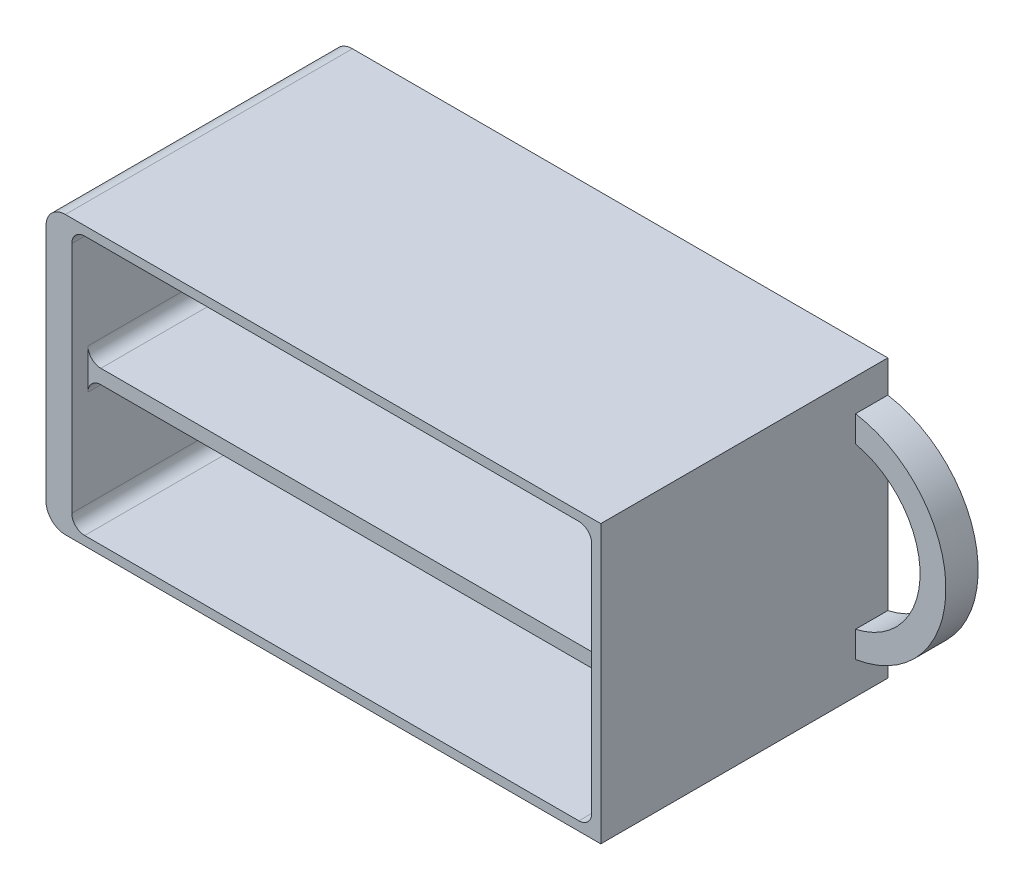
SolidWorks part; units mm, degrees
ref_plane "Спереди" through (0, 0, 0) normal (0, 0, 1) x (1, 0, 0)
ref_plane "Сверху" through (0, 0, 0) normal (0, 1, 0) x (1, 0, 0)
ref_plane "Справа" through (0, 0, 0) normal (1, 0, 0) x (0, 0, -1)
ref_plane "Плоскость4" through (0, 0, 22.25) normal (0, 0, 1) x (1, 0, 0)
sketch "Эскиз1" plane through (0, 0, 22.25) normal (0, 0, 1) x (1, 0, 0)
  line L0 (90, -21.5) -> (90, 21.5)
  line L1 (90, 21.5) -> (4, 21.5)
  line L2 (4, 21.5) -> (4, -21.5)
  line L3 (4, -21.5) -> (90, -21.5)
extrude "Бобышка-Вытянуть1" add sketch "Эскиз1" against normal blind 39.5
sketch "Эскиз2" plane through (0, 0, -17.25) normal (0, 0, -1) x (-1, 0, 0)
  line L0 (-90, -21.5) -> (-90, -16.5)
  line L1 (-90, 16.5) -> (-90, 21.5)
  line L2 (-90, 21.5) -> (-4, 21.5)
  line L3 (-4, 21.5) -> (-4, -21.5)
  line L4 (-4, -21.5) -> (-90, -21.5)
  line L5 (-90, -12.4284) -> (-90, 12.4284)
  arc A0 (-90, -16.5) -> (-90, 16.5) centre (-87.2768, 0) cw
  arc A1 (-90, 12.4284) -> (-90, -12.4284) centre (-87.2768, 0) ccw
extrude "Бобышка-Вытянуть2" add sketch "Эскиз2" along normal blind 5
sketch "Эскиз3" plane through (0, 0, 22.25) normal (0, 0, 1) x (1, 0, 0)
  line L0 (88.6, -20.1) -> (88.6, 20.1)
  line L1 (88.6, 20.1) -> (8, 20.1)
  line L2 (8, 20.1) -> (8, -20.1)
  line L3 (8, -20.1) -> (88.6, -20.1)
extrude "Вырез-Вытянуть1" cut sketch "Эскиз3" against normal blind 43.6
hole_wizard "Диаметр отверстия Ø8.3 (8.3)1" positions "Эскиз5" profile "Эскиз4" hole size "Ø8.3" standard "Ansi Metric"
sketch "Эскиз5" plane through (4, 0, 0) normal (-1, 0, 0) x (0, 0, 1)
  point P0 (0, 0)
sketch "Эскиз4" plane through (4, 0, 0) normal (0, 1, 0) x (0, 0, 1)
  line L0 (0, 0) -> (0, 3.2)
  line L1 (0, 3.2) -> (4.15, 3.2)
  line L2 (4.15, 3.2) -> (4.15, 0)
  line L5 (4.15, 0) -> (0, 0)
  line L10 (0, 3.2) -> (-4.15, 3.2) construction
  line L11 (0, -6.35) -> (0, 107.95) construction
  dimension "Диаметр отверстия" = 8.3
  dimension "Глубина отверстия" = 3.2
  dimension "Угол заточки сверла" = 180
fillet "Скругление1" radius 3 2 edges at (4, -21.5, 0) (4, 21.5, 0)
sketch "Эскиз6" plane through (4, 0, 0) normal (-1, 0, 0) x (0, 0, 1)
  circle A0 centre (0, 0) radius 4.15 construction
  circle A1 centre (0, 0) radius 4.15
extrude "Бобышка-Вытянуть3" add sketch "Эскиз6" against normal blind 4
sketch "Эскиз7" plane through (0, 0, -22.25) normal (0, 0, -1) x (-1, 0, 0)
  line L1 (-90, -12.4284) -> (-90, 12.4284) construction
  line L2 (-90, 0) -> (-3.2249, 0) construction
  line L3 (-90, -1.1) -> (-90, 1.1)
  line L4 (-4, 0) -> (-4, 1.1)
  line L5 (-4, -18.5) -> (-4, 18.5) construction
  line L6 (-4, 0) -> (-4, -1.1)
  line L7 (-90, -1.1) -> (-4, -1.1)
  line L8 (-4, 1.1) -> (-90, 1.1)
  point P0 (-90, 0)
  point P7 (-90, 0)
  dimension "D1" = 1.1
  dimension "D2" = 1.1
extrude "Бобышка-Вытянуть4" add sketch "Эскиз7" against normal blind 42
fillet "Скругление2" radius 2 16 edges at (88.6, -10.6, -21.35) (48.3, -20.1, -21.35) (8, -10.6, -21.35) (48.3, -1.1, -21.35) (8, 10.6, -21.35) (48.3, 20.1, -21.35) (88.6, 10.6, -21.35) (48.3, 1.1, -21.35) (88.6, -1.1, -0.8) (88.6, 20.1, 0.45) (88.6, 1.1, -0.8) (88.6, -20.1, 0.45) (8, -20.1, 0.45) (8, -1.1, -0.8) (8, 1.1, -0.8) (8, 20.1, 0.45)
